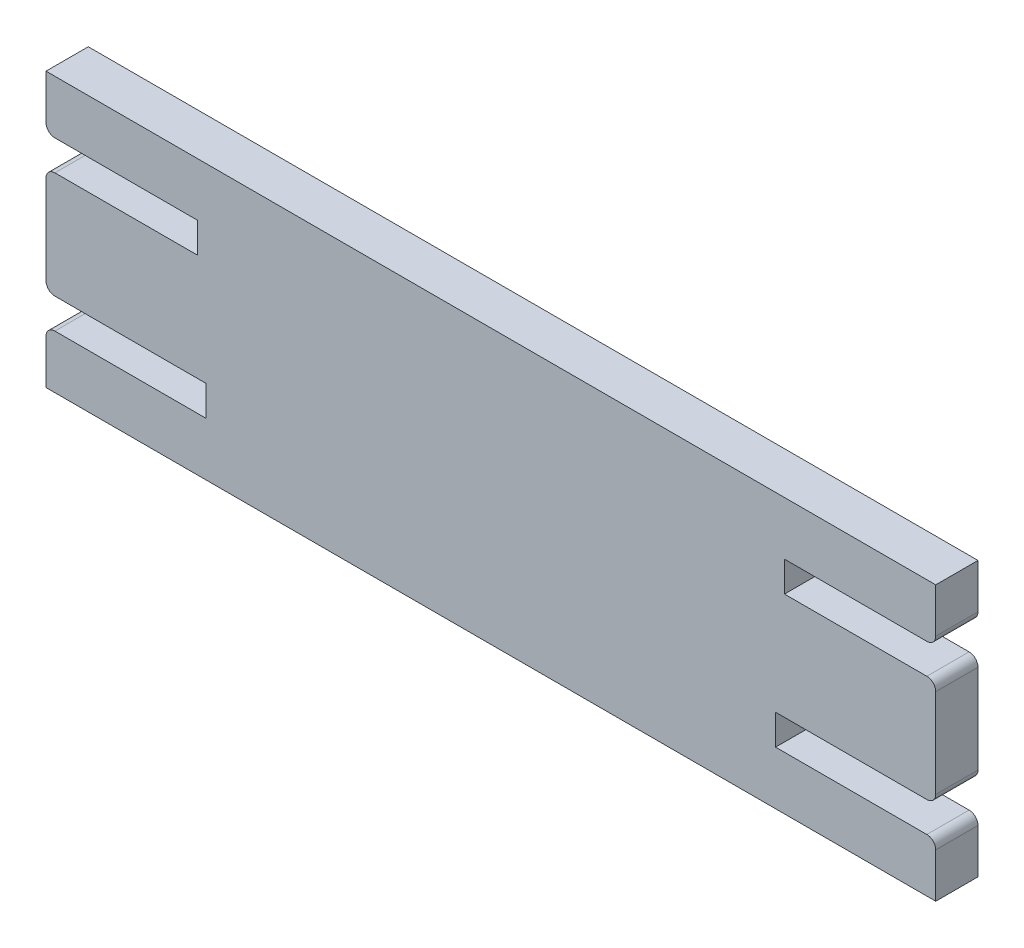
SolidWorks part; units mm, degrees
ref_plane "Front Plane" through (0, 0, 0) normal (0, 0, 1) x (1, 0, 0)
ref_plane "Top Plane" through (0, 0, 0) normal (0, 1, 0) x (1, 0, 0)
ref_plane "Right Plane" through (0, 0, 0) normal (1, 0, 0) x (0, 0, -1)
sketch "Sketch1" plane through (0, 0, 0) normal (0, 0, 1) x (1, 0, 0)
  line L0 (28.1054, -10.25) -> (28.1054, -15.25)
  line L1 (-71.8946, 15.55) -> (28.1054, 15.55)
  line L2 (-71.8946, 15.55) -> (-71.8946, 10.55)
  line L3 (-71.8946, -15.25) -> (28.1054, -15.25)
  line L4 (28.1054, 5.15) -> (28.1054, -4.85)
  line L5 (-70.8946, 9.55) -> (-54.8946, 9.55)
  line L6 (-54.8946, 9.55) -> (-54.8946, 6.15)
  line L7 (-54.8946, 6.15) -> (-70.8946, 6.15)
  line L8 (-21.8946, -15.25) -> (-21.8946, 15.55) construction
  line L9 (-53.8946, -9.25) -> (-53.8946, -5.85)
  line L10 (-53.8946, -5.85) -> (-70.8946, -5.85)
  line L11 (-70.8946, -9.25) -> (-53.8946, -9.25)
  line L12 (27.1054, -9.25) -> (10.1054, -9.25)
  line L13 (10.1054, -5.85) -> (27.1054, -5.85)
  line L14 (10.1054, -9.25) -> (10.1054, -5.85)
  line L15 (11.1054, 6.15) -> (27.1054, 6.15)
  line L16 (11.1054, 9.55) -> (11.1054, 6.15)
  line L17 (27.1054, 9.55) -> (11.1054, 9.55)
  line L18 (-71.8946, 5.15) -> (-71.8946, -4.85)
  line L19 (-71.8946, -10.25) -> (-71.8946, -15.25)
  line L20 (28.1054, 15.55) -> (28.1054, 10.55)
  arc A0 (27.1054, 9.55) -> (28.1054, 10.55) centre (27.1054, 10.55) ccw
  arc A1 (27.1054, 6.15) -> (28.1054, 5.15) centre (27.1054, 5.15) cw
  arc A2 (27.1054, -5.85) -> (28.1054, -4.85) centre (27.1054, -4.85) ccw
  arc A3 (27.1054, -9.25) -> (28.1054, -10.25) centre (27.1054, -10.25) cw
  arc A4 (-70.8946, -9.25) -> (-71.8946, -10.25) centre (-70.8946, -10.25) ccw
  arc A5 (-70.8946, -5.85) -> (-71.8946, -4.85) centre (-70.8946, -4.85) cw
  arc A6 (-70.8946, 6.15) -> (-71.8946, 5.15) centre (-70.8946, 5.15) ccw
  arc A7 (-70.8946, 9.55) -> (-71.8946, 10.55) centre (-70.8946, 10.55) cw
  point P0 (0, 0)
  point P1 (-21.8946, 0.15)
  point P10 (-21.8946, -15.25)
  point P34 (28.1054, 9.55)
  point P35 (28.1054, 6.15)
  point P36 (28.1054, -5.85)
  point P37 (28.1054, -9.25)
  point P40 (-71.8946, -9.25)
  point P43 (-71.8946, -5.85)
  point P46 (-71.8946, 6.15)
  point P49 (-71.8946, 9.55)
  point P50 (-21.8946, -15.25)
  dimension "D6" = 6
  dimension "D2" = 50
  dimension "D3" = 6
  dimension "D4" = 3.4
  dimension "D5" = 17
  dimension "D11" = 10
  dimension "D12" = 3.4
  dimension "D13" = 17
extrude "Boss-Extrude1" add sketch "Sketch1" along normal blind 4.75
